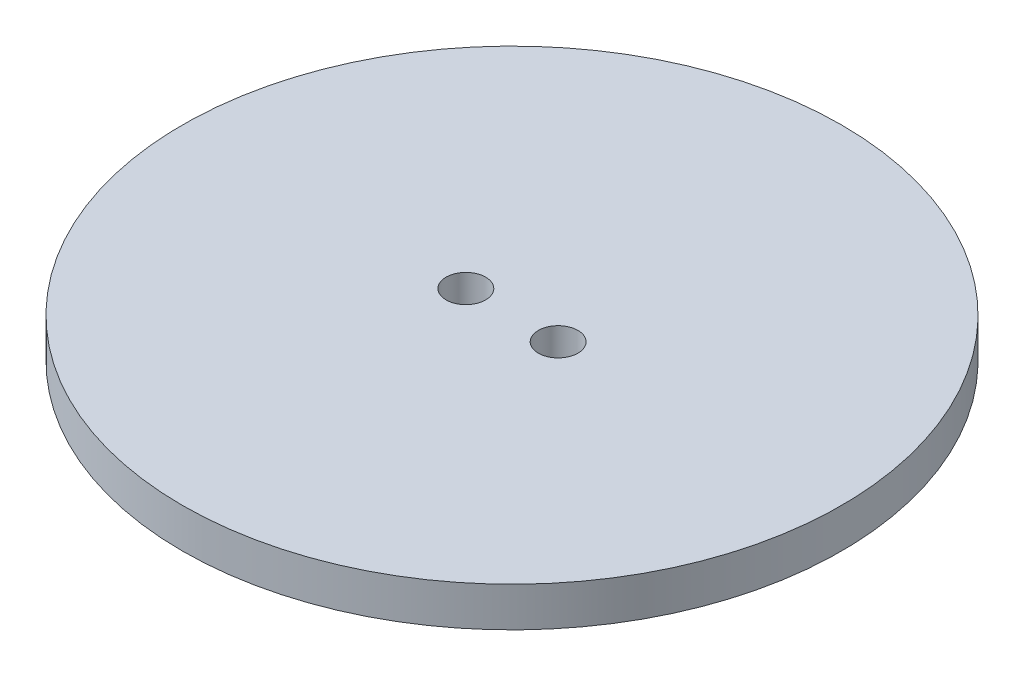
SolidWorks part; units mm, degrees
ref_plane "Plan de face" through (0, 0, 0) normal (0, 0, 1) x (1, 0, 0)
ref_plane "Plan de dessus" through (0, 0, 0) normal (0, 1, 0) x (1, 0, 0)
ref_plane "Plan de droite" through (0, 0, 0) normal (1, 0, 0) x (0, 0, -1)
sketch "Esquisse1" plane through (0, 0, 0) normal (0, 1, 0) x (1, 0, 0)
  line L0 (-3.5, 0) -> (0, 0) construction
  line L1 (2, 0) -> (3.5, 0) construction
  circle A0 centre (0, 0) radius 25
  circle A2 centre (-3.5, 0) radius 1.5
  circle A3 centre (3.5, 0) radius 1.5
  arc A10 (-1.9911, 2.8785) -> (-1.9911, -2.8785) centre (-3.5, 0) ccw construction
  circle A11 centre (0, 0) radius 8.75 construction
  circle A13 centre (0, 0) radius 16 construction
  circle A14 centre (0, 0) radius 7.5 construction
  circle A15 centre (0, -11.2781) radius 10 construction
  point P15 (0, -11.2781)
  dimension "D1" = 50
  dimension "D2" = 6.5
  dimension "D3" = 3.5
  dimension "D4" = 7
  dimension "D5" = 3
  dimension "D6" = 3
  dimension "D7" = 17.5
  dimension "D8" = 32
  dimension "D9" = 0
extrude "Boss.-Extru.1" add sketch "Esquisse1" along normal blind 3
